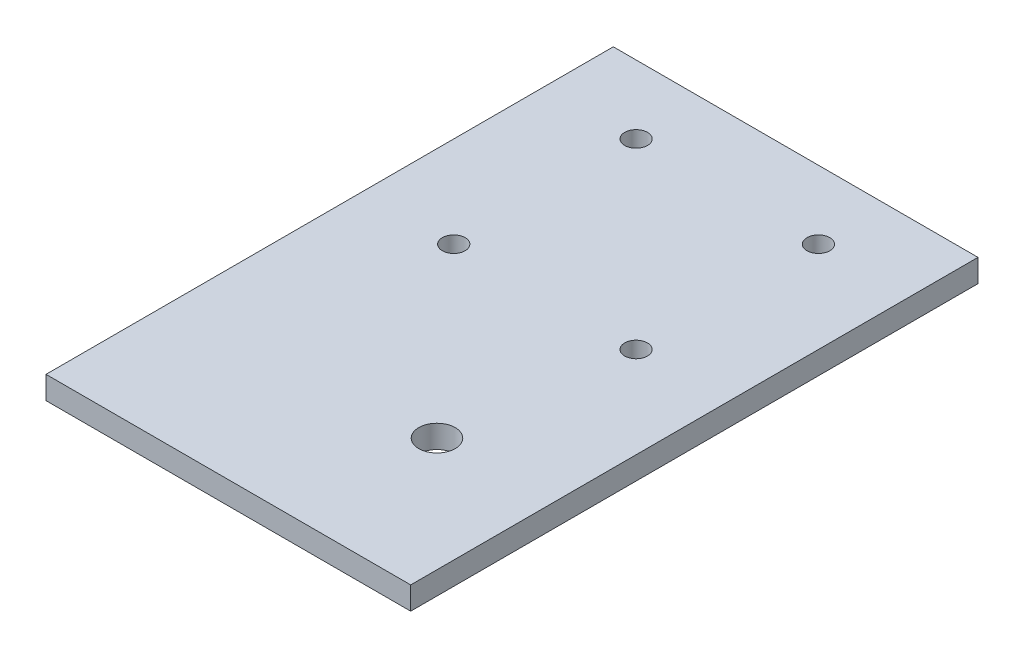
SolidWorks part; units mm, degrees
ref_plane "Front Plane" through (0, 0, 0) normal (0, 0, 1) x (1, 0, 0)
ref_plane "Top Plane" through (0, 0, 0) normal (0, 1, 0) x (1, 0, 0)
ref_plane "Right Plane" through (0, 0, 0) normal (1, 0, 0) x (0, 0, -1)
sketch "Sketch1" plane through (0, 0, 0) normal (0, 1, 0) x (1, 0, 0)
  line L0 (40, -32.054) -> (120, -32.054) construction
  line L1 (40, 2.946) -> (120, 2.946)
  line L2 (40, 2.946) -> (40, -67.054)
  line L4 (120, 2.946) -> (120, -67.054)
  line L5 (120, -32.054) -> (80, 2.946) construction
  line L6 (80, 2.946) -> (80, -67.054) construction
  line L7 (120, -90.734) -> (40, -90.734) construction
  line L9 (40, -67.054) -> (40, -121.4987)
  line L10 (40, -121.4987) -> (120, -121.4987)
  line L11 (120, -67.054) -> (120, -121.4987)
  circle A5 centre (60, -12.054) radius 2.5
  circle A6 centre (60, -52.054) radius 2.5
  circle A7 centre (100, -52.054) radius 2.5
  circle A8 centre (100, -12.054) radius 2.5
  circle A9 centre (109.2883, -32.054) radius 4 construction
  circle A10 centre (95, -90.734) radius 4
  dimension "D3" = 8
  dimension "D4" = 5
  dimension "D7" = 8
  dimension "D8" = 25
  dimension "D1" = 80
  dimension "D2" = 70
  dimension "D5" = 20
  dimension "D6" = 20
extrude "Boss-Extrude1" add sketch "Sketch1" along normal blind 5
